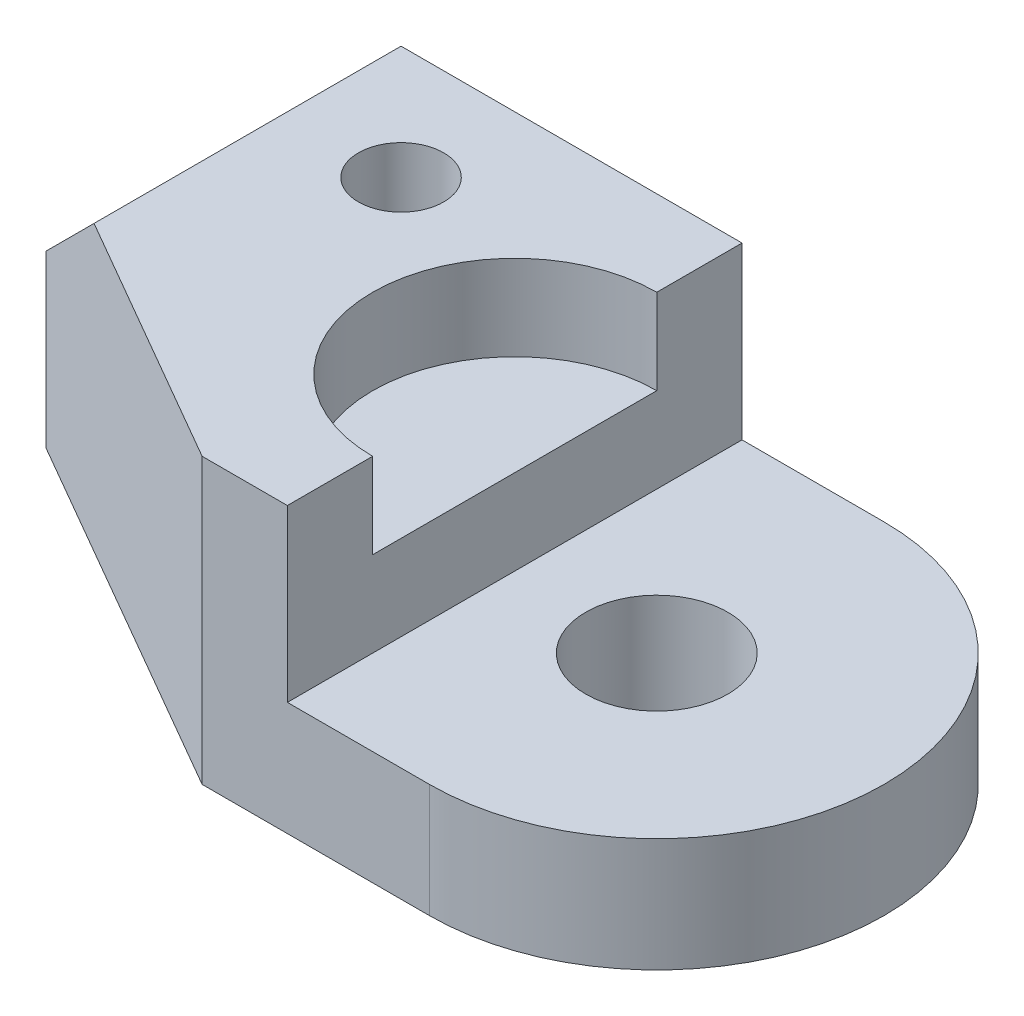
SolidWorks part; units mm, degrees
ref_plane "Front Plane" through (0, 0, 0) normal (0, 0, 1) x (1, 0, 0)
ref_plane "Top Plane" through (0, 0, 0) normal (0, 1, 0) x (1, 0, 0)
ref_plane "Right Plane" through (0, 0, 0) normal (1, 0, 0) x (0, 0, -1)
sketch "Sketch1" plane through (0, 0, 0) normal (0, 1, 0) x (1, 0, 0)
  line L0 (0, -50.8) -> (-133.35, -50.8)
  line L1 (-133.35, -50.8) -> (-133.35, 50.8)
  line L2 (-133.35, 50.8) -> (0, 50.8)
  arc A0 (0, -50.8) -> (0, 50.8) centre (0, 0) ccw
  dimension "D1" = 50.8
  dimension "D2" = 133.35
extrude "Boss-Extrude1" add sketch "Sketch1" along normal blind 63.5
sketch "Sketch2" plane through (0, 63.5, 0) normal (0, 1, 0) x (1, 0, 0)
  line L1 (-31.75, 50.8) -> (-31.75, -50.8)
  line L2 (0, 50.8) -> (-133.35, 50.8) construction
  line L3 (-133.35, -50.8) -> (0, -50.8) construction
  dimension "D1" = 31.75
extrude "Cut-Extrude1" cut sketch "Sketch2" against normal blind 38.1 and the other way through all
sketch "Sketch3" plane through (0, 63.5, 0) normal (0, 1, 0) x (1, 0, 0)
  line L0 (-31.75, -50.8) -> (-50.8, -50.8)
  line L1 (-133.35, -50.8) -> (-31.75, -50.8) construction
  line L2 (-50.8, -50.8) -> (-133.35, -3.1397)
  line L3 (-133.35, 50.8) -> (-133.35, -50.8) construction
  line L4 (-133.35, -3.1397) -> (-133.35, -50.8)
  line L5 (-133.35, -50.8) -> (-50.8, -50.8)
  line M3 (-133.35, -50.8) -> (-31.75, -50.8)
  line M6 (-133.35, 50.8) -> (-133.35, -50.8)
  dimension "D1" = 19.05
  dimension "D2" = 60
extrude "Cut-Extrude2" cut sketch "Sketch3" against normal through all contours L2 M3 M6
sketch "Sketch4" plane through (0, 0, -50.8) normal (0, 0, -1) x (-1, 0, 0)
  line L0 (133.35, 63.5) -> (107.95, 63.5)
  line L1 (31.75, 63.5) -> (133.35, 63.5) construction
  line L2 (107.95, 63.5) -> (133.35, 38.1)
  line L3 (133.35, 63.5) -> (133.35, 0) construction
  line L4 (133.35, 38.1) -> (133.35, 63.5)
  dimension "D1" = 76.2
  dimension "D2" = 45
extrude "Cut-Extrude3" cut sketch "Sketch4" against normal through all
sketch "Sketch5" plane through (0, 63.5, 0) normal (0, 1, 0) x (1, 0, 0)
  line L0 (-31.75, 50.8) -> (-31.75, -50.8) construction
  circle A0 centre (-31.75, 0) radius 31.75
  dimension "D1" = 63.5
extrude "Cut-Extrude4" cut sketch "Sketch5" against normal blind 19.05
sketch "Sketch6" plane through (0, 63.5, 0) normal (0, 1, 0) x (1, 0, 0)
  line L0 (-31.75, 50.8) -> (-107.95, 50.8) construction
  circle A0 centre (-82.55, 25.4) radius 9.525
  dimension "D3" = 19.05
  dimension "D1" = 50.8
  dimension "D2" = 25.4
extrude "Cut-Extrude5" cut sketch "Sketch6" against normal through all
sketch "Sketch7" plane through (0, 25.4, 0) normal (0, 1, 0) x (1, 0, 0)
  circle A0 centre (0, 0) radius 15.875
  dimension "D1" = 31.75
extrude "Cut-Extrude6" cut sketch "Sketch7" against normal through all
